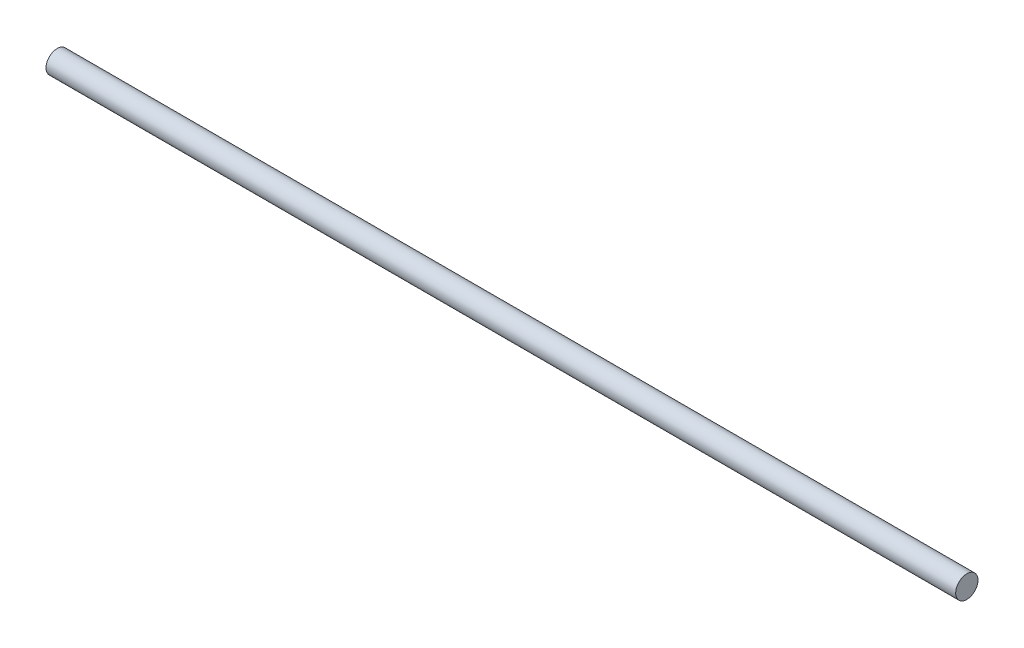
SolidWorks part; units mm, degrees
ref_plane "Plan de face" through (0, 0, 0) normal (0, 0, 1) x (1, 0, 0)
ref_plane "Plan de dessus" through (0, 0, 0) normal (0, 1, 0) x (1, 0, 0)
ref_plane "Plan de droite" through (0, 0, 0) normal (1, 0, 0) x (0, 0, -1)
ref_plane "Plan1" through (0, 0, 0) normal (0, 0, -1) x (-1, 0, 0)
sketch "Esquisse1" plane through (0, 0, 0) normal (0, 0, -1) x (-1, 0, 0)
  line L0 (-163, 4) -> (-163, 0)
  line L1 (-163, 0) -> (163, 0)
  line L2 (163, 0) -> (163, 4)
  line L3 (163, 4) -> (-163, 4)
  line L4 (-163, 0) -> (163, 0) construction
revolve "Révolution1" add sketch "Esquisse1" angle 360 about L4
